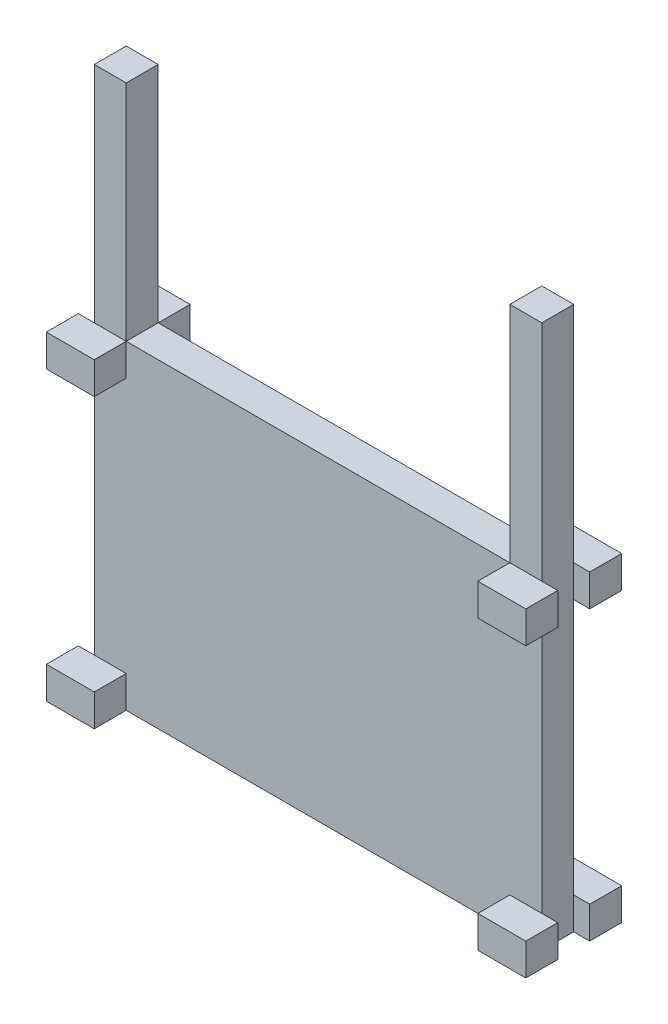
SolidWorks part; units mm, degrees
ref_plane "Front" through (0, 0, 0) normal (0, 0, 1) x (1, 0, 0)
ref_plane "Top" through (0, 0, 0) normal (0, 1, 0) x (1, 0, 0)
ref_plane "Right" through (0, 0, 0) normal (1, 0, 0) x (0, 0, -1)
sketch "Sketch1" plane through (0, 0, 0) normal (0, 0, 1) x (1, 0, 0)
  line L1 (0, 0) -> (-35.56, 0)
  line L2 (0, 0) -> (0, 25.4)
  line L3 (0, 25.4) -> (-35.56, 25.4)
  line L4 (-35.56, 0) -> (-35.56, 25.4)
  dimension "D1" = 35.56
  dimension "D2" = 25.4
extrude "Boss-Extrude1" add sketch "Sketch1" along normal blind 2.54
sketch "Sketch2" plane through (0, 0, 2.54) normal (0, 0, 1) x (1, 0, 0)
  line L1 (-35.56, 25.4) -> (-33.02, 25.4)
  line L2 (-35.56, 25.4) -> (-35.56, 22.86)
  line L3 (-35.56, 22.86) -> (-33.02, 22.86)
  line L4 (-33.02, 25.4) -> (-33.02, 22.86)
  line L5 (0, 25.4) -> (-2.54, 25.4)
  line L6 (0, 25.4) -> (0, 22.86)
  line L7 (0, 22.86) -> (-2.54, 22.86)
  line L8 (-2.54, 25.4) -> (-2.54, 22.86)
  line L9 (0, 0) -> (-2.54, 0)
  line L10 (0, 0) -> (0, 2.54)
  line L11 (0, 2.54) -> (-2.54, 2.54)
  line L12 (-2.54, 0) -> (-2.54, 2.54)
  line L13 (-35.56, 0) -> (-33.02, 0)
  line L14 (-35.56, 0) -> (-35.56, 2.54)
  line L15 (-35.56, 2.54) -> (-33.02, 2.54)
  line L16 (-33.02, 0) -> (-33.02, 2.54)
  dimension "D1" = 2.54
  dimension "D2" = 2.54
  dimension "D3" = 2.54
  dimension "D4" = 2.54
  dimension "D5" = 2.54
  dimension "D6" = 2.54
  dimension ".1" = 2.54
  dimension "D7" = 2.54
extrude "Boss-Extrude2" add sketch "Sketch2" along normal blind 2.54
ref_plane "Plane1" through (0, 0, 1.27) normal (0, 0, 1) x (1, 0, 0)
mirror "Mirror1" about plane through (0, 0, 1.27) normal (0, 0, 1) of "Boss-Extrude2"
sketch "Sketch4" plane through (-35.56, 0, 0) normal (-1, 0, 0) x (0, 0, 1)
  line L1 (5.08, 25.4) -> (2.54, 25.4)
  line L2 (5.08, 25.4) -> (5.08, 22.86)
  line L3 (5.08, 22.86) -> (2.54, 22.86)
  line L4 (2.54, 25.4) -> (2.54, 22.86)
  line L5 (-2.54, 25.4) -> (0, 25.4)
  line L6 (-2.54, 25.4) -> (-2.54, 22.86)
  line L7 (-2.54, 22.86) -> (0, 22.86)
  line L8 (0, 25.4) -> (0, 22.86)
  line L9 (5.08, 0) -> (2.54, 0)
  line L10 (5.08, 0) -> (5.08, 2.54)
  line L11 (5.08, 2.54) -> (2.54, 2.54)
  line L12 (2.54, 0) -> (2.54, 2.54)
  line L13 (-2.54, 0) -> (0, 0)
  line L14 (-2.54, 0) -> (-2.54, 2.54)
  line L15 (-2.54, 2.54) -> (0, 2.54)
  line L16 (0, 0) -> (0, 2.54)
extrude "Boss-Extrude4" add sketch "Sketch4" along normal blind 1.27
ref_plane "Plane2" through (-17.78, 0, 0) normal (-1, 0, 0) x (0, 0, 1)
mirror "Mirror2" about plane through (-17.78, 0, 0) normal (-1, 0, 0) of "Boss-Extrude4"
ref_plane "Plane3" through (0, 12.7, 0) normal (0, -1, 0) x (-1, 0, 0)
sketch "Sketch5" plane through (0, 25.4, 0) normal (0, 1, 0) x (1, 0, 0)
  line L1 (-35.56, -2.54) -> (-33.02, -2.54)
  line L2 (-35.56, -2.54) -> (-35.56, 0)
  line L3 (-35.56, 0) -> (-33.02, 0)
  line L4 (-33.02, -2.54) -> (-33.02, 0)
  line L5 (0, -2.54) -> (-2.54, -2.54)
  line L6 (0, -2.54) -> (0, 0)
  line L7 (0, 0) -> (-2.54, 0)
  line L8 (-2.54, -2.54) -> (-2.54, 0)
extrude "Boss-Extrude5" add sketch "Sketch5" along normal blind 17.78
